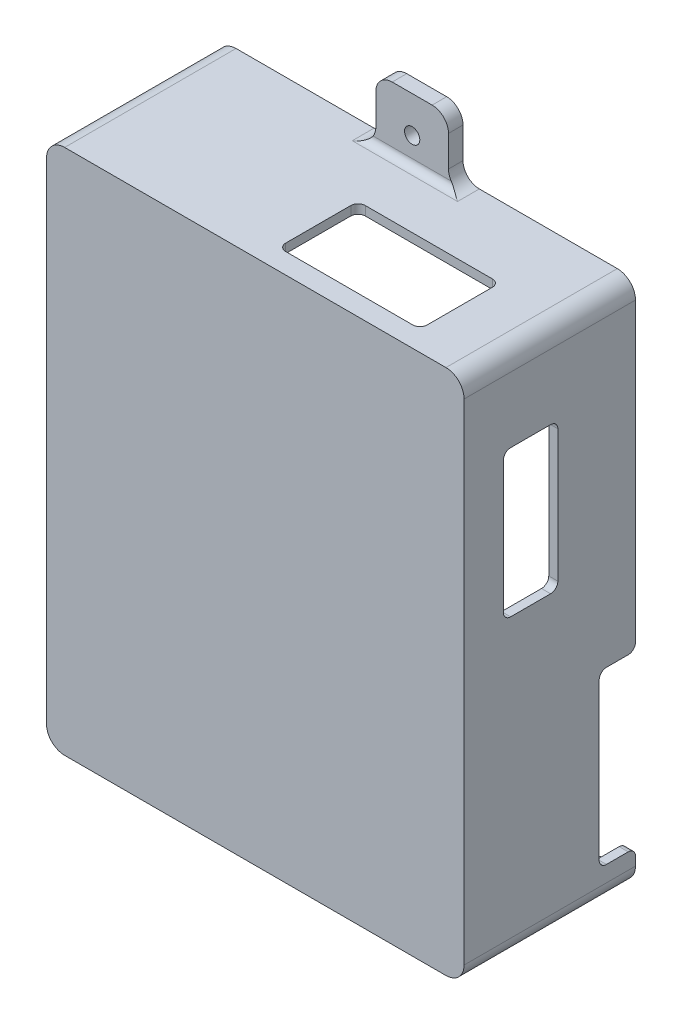
SolidWorks part; units mm, degrees
ref_plane "Front Plane" through (0, 0, 0) normal (0, 0, 1) x (1, 0, 0)
ref_plane "Top Plane" through (0, 0, 0) normal (0, 1, 0) x (1, 0, 0)
ref_plane "Right Plane" through (0, 0, 0) normal (1, 0, 0) x (0, 0, -1)
sketch "Sketch1" plane through (0, 0, 0) normal (0, 0, 1) x (1, 0, 0)
  line L0 (99.1678, -10.6824) -> (107.5623, -10.6824) construction
  line L1 (104.1678, -15.6824) -> (104.1678, -10.0031) construction
  line L2 (104.1678, -141.9936) -> (104.1678, -164.3835) construction
  line L4 (94.782, -150.6824) -> (109.8238, -150.6824) construction
  line L7 (104.1678, -150.6824) -> (-5.8322, -150.6824)
  line L8 (104.1678, -150.6824) -> (104.1678, -10.6824)
  line L9 (104.1678, -10.6824) -> (-5.8322, -10.6824)
  line L10 (-5.8322, -150.6824) -> (-5.8322, -10.6824)
  point P12 (104.1678, -150.6824)
  point P15 (104.1678, -10.6824)
  dimension "D1" = 140
  dimension "D2" = 110
extrude "Boss-Extrude2" add sketch "Sketch1" along normal blind 2.5
sketch "Sketch2" plane through (0, -150.6824, 0) normal (0, -1, 0) x (1, 0, 0)
  line L1 (-5.8322, 2.5) -> (104.1678, 2.5)
  line L2 (-5.8322, 2.5) -> (-5.8322, -44.7)
  line L3 (-5.8322, -44.7) -> (104.1678, -44.7)
  line L4 (104.1678, 2.5) -> (104.1678, -44.7)
  dimension "D1" = 47.2
extrude "Boss-Extrude3" add sketch "Sketch2" along normal blind 2.5
sketch "Sketch3" plane through (0, -10.6824, 0) normal (0, 1, 0) x (1, 0, 0)
  line L1 (104.1678, -2.5) -> (-5.8322, -2.5)
  line L2 (104.1678, -2.5) -> (104.1678, 44.7)
  line L3 (104.1678, 44.7) -> (-5.8322, 44.7)
  line L4 (-5.8322, -2.5) -> (-5.8322, 44.7)
  dimension "D1" = 47.2
extrude "Boss-Extrude4" add sketch "Sketch3" along normal blind 2.5
sketch "Sketch4" plane through (104.1678, 0, 0) normal (1, 0, 0) x (0, 0, -1)
  line L1 (-2.5, -153.1824) -> (44.7, -153.1824)
  line L2 (-2.5, -153.1824) -> (-2.5, -8.1824)
  line L3 (-2.5, -8.1824) -> (44.7, -8.1824)
  line L4 (44.7, -153.1824) -> (44.7, -8.1824)
  dimension "D1" = 47.2
extrude "Boss-Extrude5" add sketch "Sketch4" along normal blind 2.5
sketch "Sketch7" plane through (-5.8322, 0, 0) normal (-1, 0, 0) x (0, 0, 1)
  line L1 (2.5, -8.1824) -> (-44.7, -8.1824)
  line L2 (2.5, -8.1824) -> (2.5, -153.1824)
  line L3 (2.5, -153.1824) -> (-44.7, -153.1824)
  line L4 (-44.7, -8.1824) -> (-44.7, -15.7572)
  line L5 (2.5, -80.6824) -> (-44.7, -80.6824) construction
  line L6 (-44.7, -15.7572) -> (-39.7, -15.7572)
  line L7 (-39.7, -15.7572) -> (-39.7, -63.4628)
  line L8 (-39.7, -63.4628) -> (-44.7, -63.4628)
  line L9 (-43.701, -63.4628) -> (-44.7, -63.4628) construction
  line L10 (-44.7, -63.4628) -> (-44.7, -97.902)
  line L11 (-39.7, -97.902) -> (-44.7, -97.902)
  line L12 (-39.7, -145.6076) -> (-39.7, -97.902)
  line L13 (-44.7, -145.6076) -> (-39.7, -145.6076)
  line L14 (-44.7, -145.6076) -> (-44.7, -153.1824)
  dimension "D1" = 47.2
  dimension "D2" = 5
  dimension "D3" = 47.7056
extrude "Boss-Extrude6" add sketch "Sketch7" along normal blind 2.5
fillet "Fillet1" radius 5 8 edges at (104.1678, -10.6824, -22.35) (-5.8322, -10.6824, -22.35) (-5.8322, -150.6824, -22.35) (104.1678, -150.6824, -22.35) (-8.3322, -153.1824, -21.1) (106.6678, -153.1824, -21.1) (-8.3322, -8.1824, -21.1) (106.6678, -8.1824, -21.1)
sketch "Sketch8" plane through (0, 0, -44.7) normal (0, 0, 1) x (1, 0, 0)
  line L0 (49.1678, 9.3176) -> (49.1678, -8.1824) construction
  line L2 (-3.3322, -8.1824) -> (101.6678, -8.1824) construction
  line L3 (39.1678, 9.3176) -> (39.1678, -8.1824)
  line L4 (59.1678, 9.3176) -> (59.1678, -8.1824)
  line L5 (39.1678, 9.3176) -> (59.1678, 9.3176)
  line L6 (39.1678, -8.1824) -> (59.1678, -8.1824)
  line L7 (39.1678, -170.6824) -> (39.1678, -153.1824)
  line L8 (101.6678, -153.1824) -> (-3.3322, -153.1824) construction
  line L9 (39.1678, -170.6824) -> (59.1678, -170.6824)
  line L10 (59.1678, -170.6824) -> (59.1678, -153.1824)
  line L11 (59.1678, -153.1824) -> (39.1678, -153.1824)
  circle A0 centre (49.1678, -0.6824) radius 2.1
  circle A1 centre (49.1678, -160.6824) radius 2.1
  dimension "D1" = 4.2
  dimension "D2" = 4.2
  dimension "D3" = 10
  dimension "D4" = 10
extrude "Boss-Extrude7" add sketch "Sketch8" along normal blind 4
fillet "Fillet2" radius 4.5 8 edges at (59.1678, -153.1824, -42.7) (59.1678, -170.6824, -42.7) (39.1678, -170.6824, -42.7) (39.1678, -153.1824, -42.7) (39.1678, -8.1824, -42.7) (39.1678, 9.3176, -42.7) (59.1678, 9.3176, -42.7) (59.1678, -8.1824, -42.7)
fillet "Fillet3" radius 2 8 edges at (-7.0822, -145.6076, -44.7) (-7.0822, -145.6076, -39.7) (-7.0822, -15.7572, -44.7) (-7.0822, -15.7572, -39.7) (-7.0822, -97.902, -39.7) (-7.0822, -63.4628, -39.7) (-7.0822, -97.902, -44.7) (-7.0822, -63.4628, -44.7)
fillet "Fillet4" radius 2 2 edges at (49.1678, -153.1824, -40.7) (49.1678, -8.1824, -40.7)
sketch "Sketch10" plane through (0, -153.1824, 0) normal (0, -1, 0) x (1, 0, 0)
  line L1 (5.2905, -34.7) -> (32.4794, -34.7)
  line L2 (5.2905, -34.7) -> (5.2905, -44.7)
  line L3 (5.2905, -44.7) -> (32.4794, -44.7)
  line L4 (32.4794, -34.7) -> (32.4794, -44.7)
  line L6 (68.2938, -34.7) -> (95.4827, -34.7)
  line L7 (68.2938, -34.7) -> (68.2938, -44.7)
  line L8 (68.2938, -44.7) -> (95.4827, -44.7)
  line L9 (95.4827, -34.7) -> (95.4827, -44.7)
  dimension "D1" = 10
  dimension "D2" = 27.1889
  dimension "D3" = 10
  dimension "D4" = 27.1889
extrude "Cut-Extrude1" cut sketch "Sketch10" against normal blind 2.5
sketch "Sketch11" plane through (0, -8.1824, 0) normal (0, 1, 0) x (1, 0, 0)
  line L0 (96.4202, 21.475) -> (44.855, 21.475) construction
  line L2 (89.6699, 4.7866) -> (59.2933, 4.7866)
  line L3 (89.6699, 4.7866) -> (89.6699, 21.475)
  line L4 (89.6699, 21.475) -> (59.2933, 21.475)
  line L5 (59.2933, 4.7866) -> (59.2933, 21.475)
extrude "Boss-Extrude8" add sketch "Sketch11" against normal blind 2.5
sketch "Sketch13" plane through (106.6678, 0, 0) normal (1, 0, 0) x (0, 0, -1)
  line L0 (44.7, -148.1824) -> (44.7, -13.1824) construction
  line L1 (34.7, -143.7836) -> (44.7, -143.7836)
  line L2 (34.7, -143.7836) -> (34.7, -96.7836)
  line L3 (34.7, -96.7836) -> (44.7, -96.7836)
  line L4 (44.7, -143.7836) -> (44.7, -96.7836)
  line L10 (8.3163, -71.5378) -> (23.3163, -71.5378)
  line L11 (8.3163, -71.5378) -> (8.3163, -31.2022)
  line L12 (8.3163, -31.2022) -> (23.3163, -31.2022)
  line L13 (23.3163, -71.5378) -> (23.3163, -31.2022)
  dimension "D1" = 47
  dimension "D2" = 10
  dimension "D3" = 21.3837
  dimension "D4" = 15
  dimension "D5" = 40.3356
extrude "Cut-Extrude2" cut sketch "Sketch13" against normal blind 2.5
sketch "Sketch14" plane through (0, -8.1824, 0) normal (0, 1, 0) x (1, 0, 0)
  line L0 (101.6678, 44.7) -> (63.6678, 44.7) construction
  line L1 (88.9199, 3.0991) -> (49.9178, 3.0991)
  line L2 (88.9199, 3.0991) -> (88.9199, 25.0377)
  line L3 (88.9199, 25.0377) -> (49.9178, 25.0377)
  line L4 (49.9178, 3.0991) -> (49.9178, 25.0377)
  dimension "D1" = 19.6623
  dimension "D2" = 21.9387
  dimension "D3" = 39.002
extrude "Cut-Extrude3" cut sketch "Sketch14" against normal blind 2.5
fillet "Fillet5" radius 2 20 edges at (5.2905, -151.9324, -44.7) (5.2905, -151.9324, -34.7) (32.4794, -151.9324, -34.7) (32.4794, -151.9324, -44.7) (68.2938, -151.9324, -44.7) (68.2938, -151.9324, -34.7) (95.4827, -151.9324, -34.7) (95.4827, -151.9324, -44.7) (105.4178, -143.7836, -34.7) (105.4178, -96.7836, -34.7) (105.4178, -96.7836, -44.7) (105.4178, -143.7836, -44.7) (105.4178, -71.5378, -8.3163) (105.4178, -31.2022, -8.3163) (105.4178, -31.2022, -23.3163) (105.4178, -71.5378, -23.3163) (88.9199, -9.4324, -25.0377) (88.9199, -9.4324, -3.0991) (49.9178, -9.4324, -3.0991) (49.9178, -9.4324, -25.0377)
